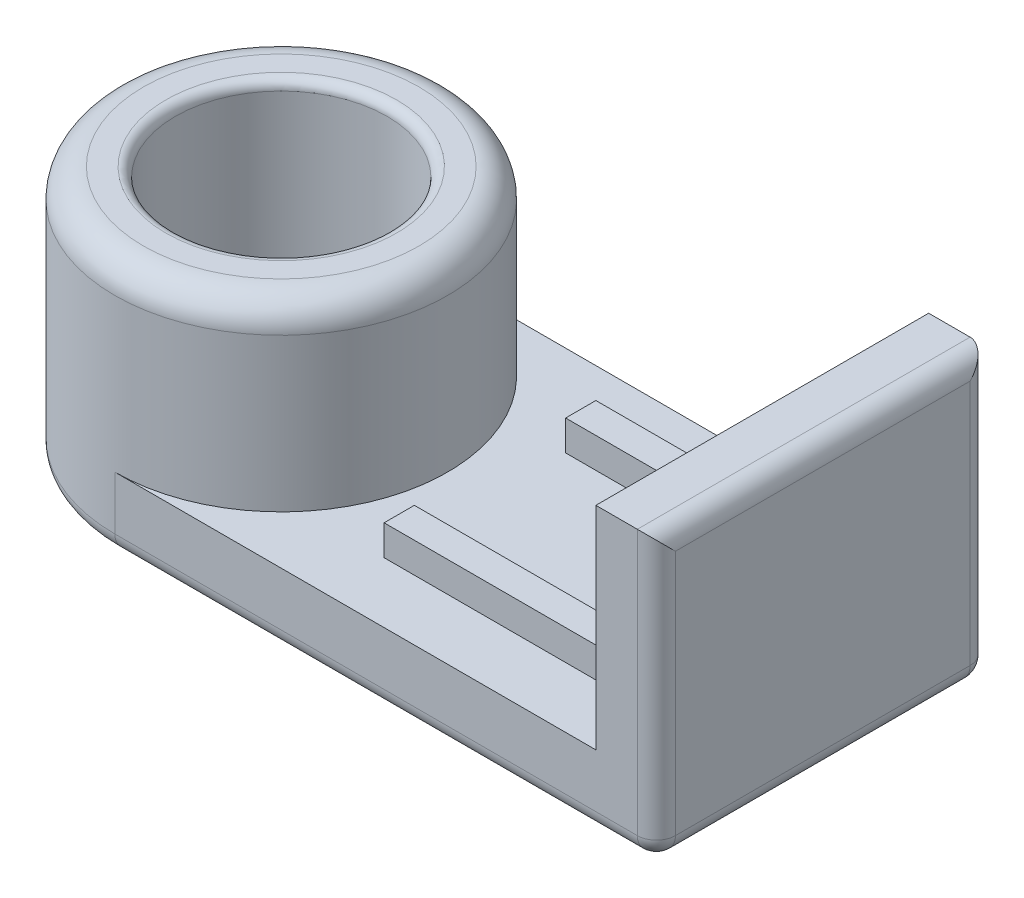
SolidWorks part; units mm, degrees
ref_plane "Front Plane" through (0, 0, 0) normal (0, 0, 1) x (1, 0, 0)
ref_plane "Top Plane" through (0, 0, 0) normal (0, 1, 0) x (1, 0, 0)
ref_plane "Right Plane" through (0, 0, 0) normal (1, 0, 0) x (0, 0, -1)
sketch "Sketch1" plane through (0, 0, 0) normal (0, 1, 0) x (1, 0, 0)
  line L0 (-19.685, 17.4625) -> (-19.685, -17.4625) construction
  line L2 (37.1475, -17.4625) -> (37.1475, 17.4625)
  line L4 (-19.685, 17.4625) -> (37.1475, 17.4625)
  line L7 (-19.685, -17.4625) -> (37.1475, -17.4625)
  arc A0 (-19.685, 17.4625) -> (-19.685, -17.4625) centre (-19.685, 0) ccw
  point P0 (0, 0)
extrude "Boss-Extrude1" add sketch "Sketch1" along normal blind 7.62
sketch "Sketch4" plane through (0, 7.62, 0) normal (0, 1, 0) x (1, 0, 0)
  line L0 (-19.685, -17.4625) -> (37.1475, -17.4625) construction
  line L1 (37.1475, 17.4625) -> (30.7975, 17.4625)
  line L2 (37.1475, 17.4625) -> (37.1475, -17.4625)
  line L3 (37.1475, -17.4625) -> (30.7975, -17.4625)
  line L4 (30.7975, 17.4625) -> (30.7975, -17.4625)
  dimension "D1" = 6.35
extrude "Boss-Extrude3" add sketch "Sketch4" along normal blind 12.7
sketch "Sketch5" plane through (0, 7.62, 0) normal (0, 1, 0) x (1, 0, 0)
  line L0 (-19.685, 17.4625) -> (-19.685, -17.4625) construction
  circle A0 centre (-19.685, 0) radius 11.1125
extrude "Cut-Extrude1" cut sketch "Sketch5" against normal blind 12.7
sketch "Sketch6" plane through (0, 7.62, 0) normal (0, 1, 0) x (1, 0, 0)
  line L1 (27.6225, 11.1125) -> (2.2225, 11.1125)
  line L2 (27.6225, 11.1125) -> (27.6225, 7.9375)
  line L3 (27.6225, 7.9375) -> (2.2225, 7.9375)
  line L4 (2.2225, 11.1125) -> (2.2225, 7.9375)
  dimension "D1" = 25.4
  dimension "D2" = 3.175
  dimension "D3" = 3.175
  dimension "D4" = 6.35
extrude "Boss-Extrude4" add sketch "Sketch6" along normal blind 3.175
sketch "Sketch7" plane through (0, 7.62, 0) normal (0, 1, 0) x (1, 0, 0)
  line L1 (27.6225, -11.1125) -> (2.2225, -11.1125)
  line L2 (27.6225, -11.1125) -> (27.6225, -7.9375)
  line L3 (27.6225, -7.9375) -> (2.2225, -7.9375)
  line L4 (2.2225, -11.1125) -> (2.2225, -7.9375)
  dimension "D1" = 3.175
  dimension "D2" = 25.4
  dimension "D3" = 3.175
  dimension "D4" = 6.35
extrude "Boss-Extrude5" add sketch "Sketch7" along normal blind 3.175
sketch "Sketch10" plane through (0, 20.32, 0) normal (0, 1, 0) x (1, 0, 0)
  line L1 (30.7975, 17.4625) -> (37.1475, 17.4625)
  line L2 (30.7975, 17.4625) -> (30.7975, -17.4625)
  line L3 (30.7975, -17.4625) -> (37.1475, -17.4625)
  line L4 (37.1475, 17.4625) -> (37.1475, -17.4625)
extrude "Boss-Extrude8" add sketch "Sketch10" along normal blind 9.525
fillet "Fillet1" radius 2 3 edges at (37.1475, 14.9225, 17.4625) (37.1475, 14.9225, -17.4625) (37.1475, 29.845, 0)
fillet "Fillet2" radius 2 6 edges at (36.5617, 0, -16.8767) (37.1475, 0, 0) (36.5617, 0, 16.8767) (7.7312, 0, 17.4625) (-37.1475, 0, 0) (7.7312, 0, -17.4625)
sketch "Sketch11" plane through (0, 7.62, 0) normal (0, 1, 0) x (1, 0, 0)
  circle A0 centre (-19.685, 0) radius 17.4625
extrude "Boss-Extrude9" add sketch "Sketch11" along normal blind 19.05
sketch "Sketch12" plane through (0, 7.62, 0) normal (0, -1, 0) x (-1, 0, 0)
  line L0 (30.7975, 0) -> (8.5725, 0) construction
  circle A0 centre (19.685, 0) radius 11.1125 construction
  circle A1 centre (19.685, 0) radius 11.1125
  dimension "D1" = 22.225
extrude "Cut-Extrude2" cut sketch "Sketch12" against normal through all
fillet "Fillet3" radius 1 2 edges at (-19.685, 26.67, 11.1125) (-19.685, 0, 11.1125)
fillet "Fillet4" radius 3 1 edges at (-19.685, 26.67, 17.4625)
